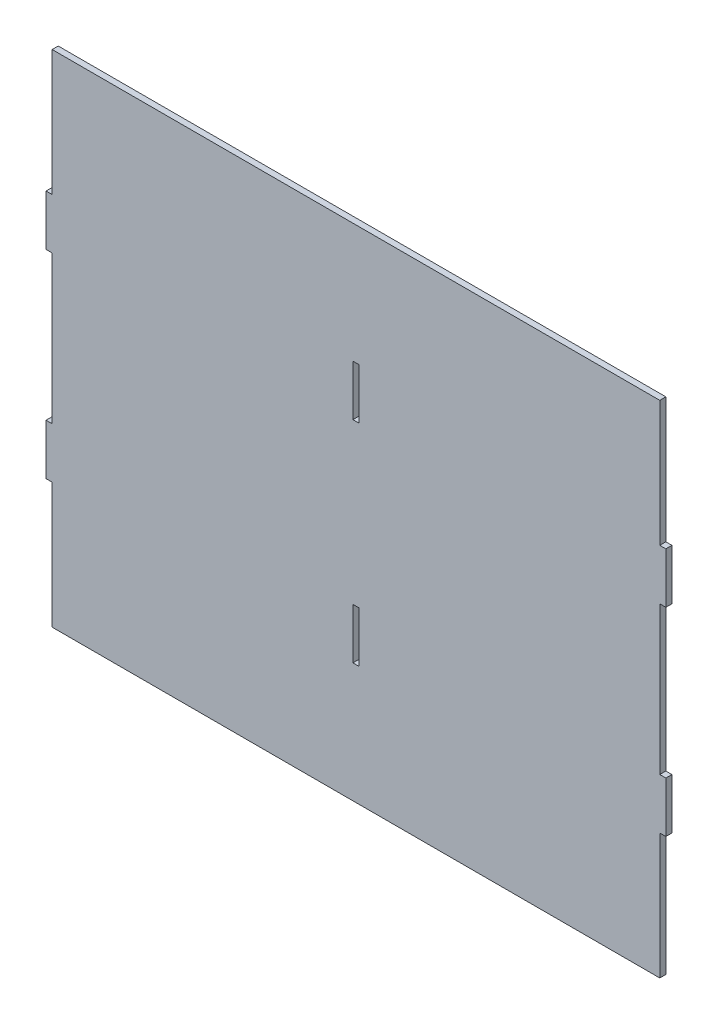
SolidWorks part; units mm, degrees
material "Maple"
ref_plane "Front Plane" through (0, 0, 0) normal (0, 0, 1) x (1, 0, 0)
ref_plane "Top Plane" through (0, 0, 0) normal (0, 1, 0) x (1, 0, 0)
ref_plane "Right Plane" through (0, 0, 0) normal (1, 0, 0) x (0, 0, -1)
sketch "Sketch1" plane through (0, 0, 0) normal (0, 0, 1) x (1, 0, 0)
  line L1 (-300, 247) -> (300, 247)
  line L2 (-300, 247) -> (-300, 123)
  line L3 (-300, -247) -> (300, -247)
  line L4 (300, 247) -> (300, 123)
  line L5 (-300, 247) -> (300, -247) construction
  line L6 (-300, -247) -> (300, 247) construction
  line L7 (-306, 123) -> (-300, 123)
  line L8 (-306, 123) -> (-306, 73)
  line L9 (-306, 73) -> (-300, 73)
  line L11 (-300, 218) -> (-282.5, 193) construction
  line L12 (-300, -123) -> (-300, -247)
  line L13 (0, 247) -> (0, -247) construction
  line L14 (306, 73) -> (300, 73)
  line L15 (306, 123) -> (306, 73)
  line L16 (306, 123) -> (300, 123)
  line L24 (-300, 73) -> (-300, -73)
  line L31 (-306, -123) -> (-300, -123)
  line L33 (300, -247) -> (300, -123)
  line L34 (300, -123) -> (306, -123)
  line L35 (-306, -123) -> (-306, -73)
  line L36 (-306, -73) -> (-300, -73)
  line L38 (300, 73) -> (300, -73)
  line L39 (300, -73) -> (306, -73)
  line L40 (306, -73) -> (306, -123)
  line L41 (0, 0) -> (-300, 0) construction
  line L42 (-3, 129) -> (3, 129)
  line L43 (-3, 129) -> (-3, 79)
  line L44 (-3, 79) -> (3, 79)
  line L45 (3, 129) -> (3, 79)
  line L46 (-3, 129) -> (3, 79) construction
  line L47 (-3, 79) -> (3, 129) construction
  line L48 (-3, -79) -> (3, -79)
  line L49 (3, -129) -> (3, -79)
  line L50 (-3, -129) -> (3, -129)
  line L51 (-3, -129) -> (-3, -79)
  point P0 (0, 0)
  point P6 (-300, 218)
  point P10 (0, 104)
  point P31 (-156.1598, -207)
  dimension "D1" = 600
  dimension "D2" = 146
  dimension "D3" = 124
  dimension "D4" = 124
  dimension "D5" = 50
  dimension "D6" = 6
  dimension "D7" = 124
  dimension "D8" = 6
  dimension "D9" = 50
  dimension "D10" = 6
  dimension "D11" = 50
  dimension "D12" = 50
  dimension "D13" = 124
  dimension "D14" = 146
  dimension "D15" = 494
  dimension "D16" = 6
  dimension "D17" = 50
  dimension "D18" = 118
  dimension "D19" = 158
extrude "Boss-Extrude1" add sketch "Sketch1" along normal blind 6
